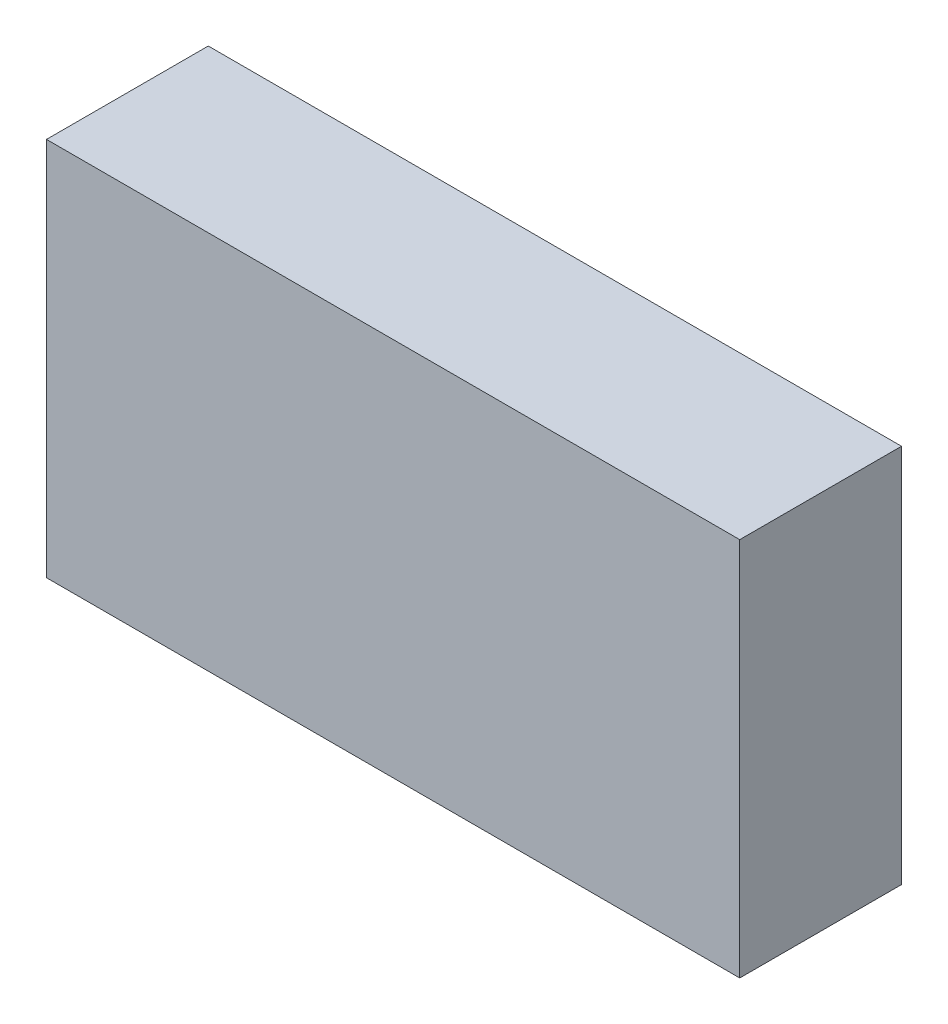
SolidWorks part; units mm, degrees
ref_plane "前视基准面" through (0, 0, 0) normal (0, 0, 1) x (1, 0, 0)
ref_plane "上视基准面" through (0, 0, 0) normal (0, 1, 0) x (1, 0, 0)
ref_plane "右视基准面" through (0, 0, 0) normal (1, 0, 0) x (0, 0, -1)
sketch "草图1" plane through (0, 0, 0) normal (0, 0, 1) x (1, 0, 0)
  line L1 (-105, -57.5) -> (105, -57.5)
  line L2 (-105, -57.5) -> (-105, 57.5)
  line L3 (-105, 57.5) -> (105, 57.5)
  line L4 (105, -57.5) -> (105, 57.5)
  line L5 (-105, -57.5) -> (105, 57.5) construction
  line L6 (-105, 57.5) -> (105, -57.5) construction
  point P0 (0, 0)
  dimension "D1" = 210
  dimension "D2" = 115
extrude "凸台-拉伸1" add sketch "草图1" along normal blind 49
